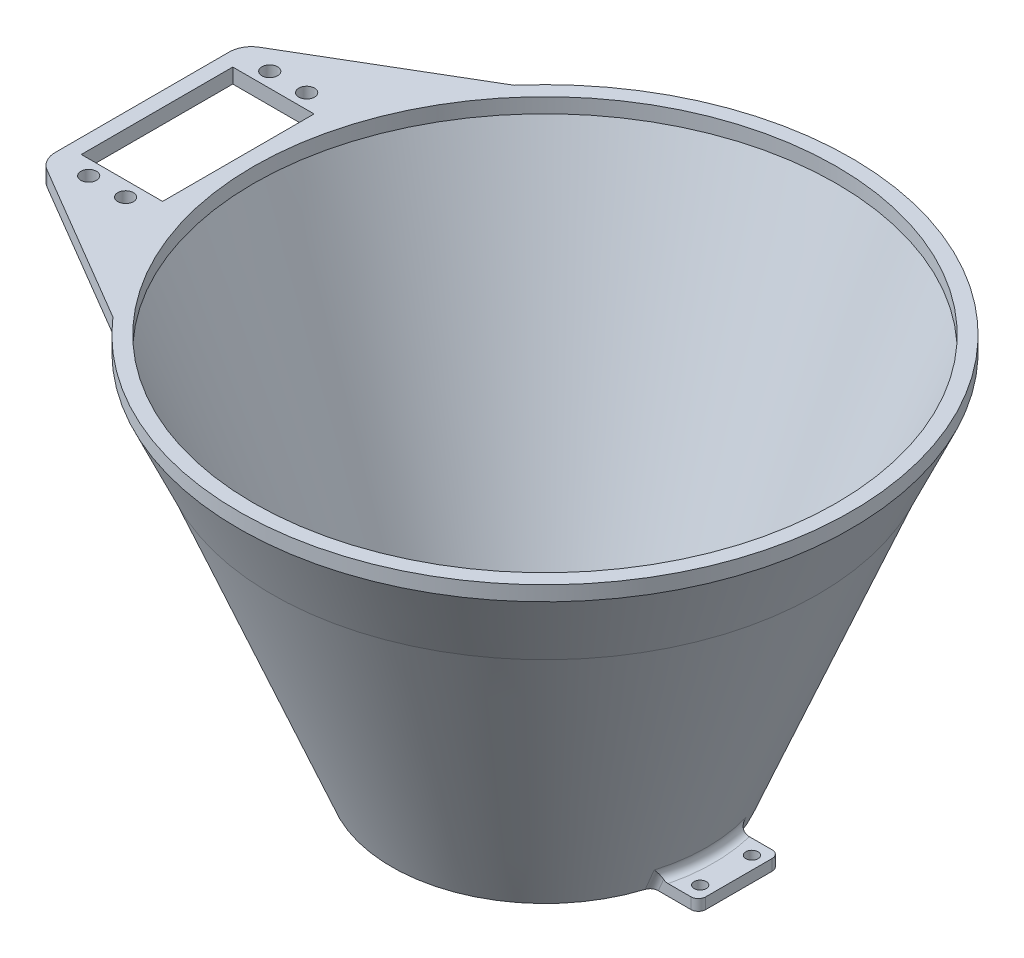
SolidWorks part; units mm, degrees
ref_plane "Front Plane" through (0, 0, 0) normal (0, 0, 1) x (1, 0, 0)
ref_plane "Top Plane" through (0, 0, 0) normal (0, 1, 0) x (1, 0, 0)
ref_plane "Right Plane" through (0, 0, 0) normal (1, 0, 0) x (0, 0, -1)
sketch "Sketch2" plane through (0, 0, 0) normal (0, 0, 1) x (1, 0, 0)
  line L0 (0, 0) -> (38.5, 0) construction
  line L1 (38.5, 0) -> (78.9026, 100)
  line L2 (38.5, 0) -> (41.5, 0) construction
  line L3 (41.5, 0) -> (81.9026, 100)
  line L4 (78.9026, 100) -> (81.9026, 100)
  line L5 (0, 0) -> (0, 42.1787) construction
  line L6 (38.5, 0) -> (41.5, 0)
  point P6 (0, 0)
  point P7 (0, 0)
  point P8 (85.1767, 100)
  dimension "D1" = 38.5
  dimension "D2" = 41.5
  dimension "D3" = 100
  dimension "D4" = 112
  dimension "D5" = 100
revolve "Revolve1" add sketch "Sketch2" angle 360 about L5
sketch "Sketch3" plane through (0, 0, 0) normal (0, -1, 0) x (1, 0, 0)
  line L0 (-52.5156, 11) -> (-40.0156, 11)
  line L1 (-52.5156, 11) -> (-52.5156, -11)
  line L2 (-52.5156, -11) -> (-40.0156, -11)
  line L3 (-52.5156, 0) -> (0, 0) construction
  line L4 (0, 0) -> (0, 25.3337) construction
  line L5 (52.5156, -11) -> (40.0156, -11)
  line L6 (52.5156, 11) -> (52.5156, -11)
  line L7 (52.5156, 11) -> (40.0156, 11)
  circle A0 centre (0, 0) radius 41.5 construction
  circle A1 centre (0, 0) radius 41.5 construction
  circle A2 centre (-49.0156, -7) radius 1.65
  arc A3 (-40.0156, -11) -> (-40.0156, 11) centre (0, 0) cw
  circle A4 centre (-49.0156, 7) radius 1.65
  circle A5 centre (49.0156, 7) radius 1.65
  arc A6 (40.0156, -11) -> (40.0156, 11) centre (0, 0) ccw
  circle A7 centre (49.0156, -7) radius 1.65
  dimension "D2" = 3.3
  dimension "D1" = 22
  dimension "D3" = 7
  dimension "D4" = 3.5
  dimension "D5" = 12.5
extrude "Boss-Extrude1" add sketch "Sketch3" against normal blind 3
fillet "Fillet1" radius 2 10 edges at (52.5156, 1.5, -11) (52.5156, 1.5, 11) (-52.5156, 1.5, 11) (-52.5156, 1.5, -11) (42.7121, 3, 0) (-42.7121, 3, 0)
sketch "Sketch4" plane through (0, 100, 0) normal (0, 1, 0) x (1, 0, 0)
  line L0 (-94, 34.5374) -> (-94, -37.4895) construction
  line L1 (-108.9765, 0) -> (0, 0) construction
  line L2 (-109, 27) -> (-20, 79.4232)
  line L3 (-105, -20.5) -> (-83, -20.5)
  line L4 (-105, -20.5) -> (-105, 20.5)
  line L5 (-105, 20.5) -> (-83, 20.5)
  line L6 (-83, -20.5) -> (-83, 20.5)
  line L7 (-105, -20.5) -> (-83, 20.5) construction
  line L8 (-105, 20.5) -> (-83, -20.5) construction
  line L9 (-109, -27) -> (-79, -27) construction
  line L10 (-109, -27) -> (-109, 27)
  line L11 (-109, 27) -> (-79, 27) construction
  line L12 (-79, -27) -> (-79, 27) construction
  line L13 (-109, -27) -> (-79, 27) construction
  line L14 (-109, 27) -> (-79, -27) construction
  line L15 (-109, -27) -> (-20, -79.4232)
  line L17 (-20, -79.4232) -> (-20, -59.4685)
  circle A0 centre (-99, 24.5) radius 2.125
  circle A1 centre (-89, 24.5) radius 2.125
  circle A2 centre (-89, -24.5) radius 2.125
  circle A3 centre (-99, -24.5) radius 2.125
  circle A4 centre (0, 0) radius 81.9026 construction
  circle A8 centre (0, 0) radius 78.9026 construction
  circle A9 centre (0, 0) radius 78.9026
  arc A10 (-59.7672, -55.9993) -> (-59.7672, 55.9993) centre (0, 0) ccw
  point P13 (-94, 0)
  point P16 (-94, 0)
  dimension "D1" = 4.25
  dimension "D2" = 5
  dimension "D3" = 24.5
  dimension "D4" = 94
  dimension "D5" = 22
  dimension "D6" = 41
  dimension "D7" = 54
  dimension "D8" = 30
  dimension "D9" = 20
extrude "Boss-Extrude2" add sketch "Sketch4" along normal blind 4 separate body
sketch "Sketch6" plane through (0, 0, 0) normal (0, 0, 1) x (1, 0, 0)
  line L0 (-81.9026, 100) -> (-82.9026, 100)
  line L1 (-109, 100) -> (-45.983, 100) construction
  line L2 (-82.9026, 100) -> (-73.8221, 80)
  line L3 (-81.9026, 100) -> (-43.8228, 5.7492) construction
  line L4 (-73.8221, 80) -> (-81.9026, 100)
  line L5 (0, 0) -> (0, 90.5033) construction
  dimension "D1" = 1
  dimension "D2" = 20
revolve "Revolve5" add sketch "Sketch6" angle 360 about L5
sketch "Sketch7" plane through (0, 100, 0) normal (0, 1, 0) x (1, 0, 0)
  line L2 (-62.6368, 54.309) -> (-45.983, 64.1186)
  line L3 (-62.6368, 54.309) -> (-45.983, 64.1186)
  line L6 (-45.983, -64.1186) -> (-62.6368, -54.309)
  line L7 (-45.983, -64.1186) -> (-62.6368, -54.309)
  arc A2 (-62.6368, -54.309) -> (-62.6368, 54.309) centre (0, 0) ccw
  arc A3 (-45.983, -64.1186) -> (-45.983, 64.1186) centre (0, 0) ccw
  arc A4 (-62.6368, -54.309) -> (-62.6368, 54.309) centre (0, 0) ccw
  arc A6 (-45.983, -64.1186) -> (-45.983, 64.1186) centre (0, 0) ccw
  dimension "D1" = 0
extrude "Boss-Extrude3" add sketch "Sketch7" along normal blind 4
fillet "Fillet5" radius 6 2 edges at (-109, 102, -27) (-109, 102, 27)
